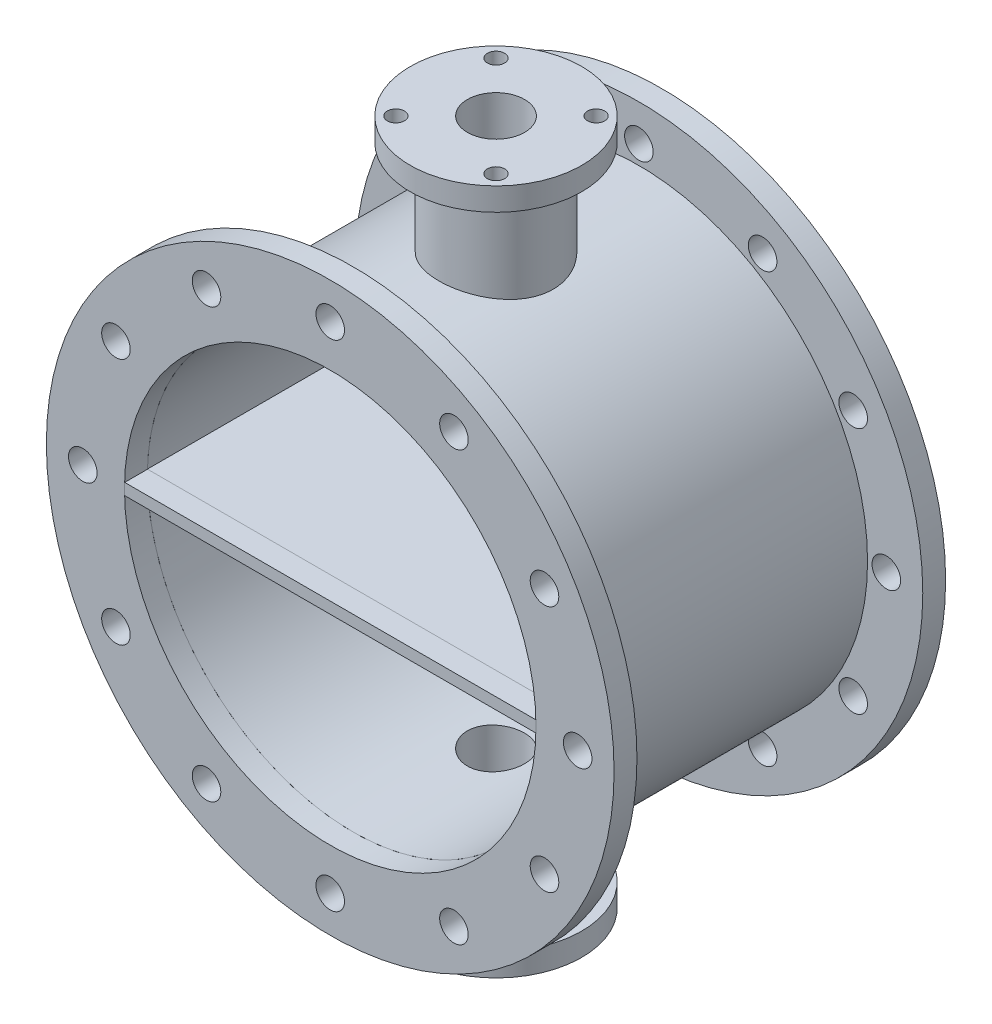
SolidWorks part; units mm, degrees
ref_plane "Front Plane" through (0, 0, 0) normal (0, 0, 1) x (1, 0, 0)
ref_plane "Top Plane" through (0, 0, 0) normal (0, 1, 0) x (1, 0, 0)
ref_plane "Right Plane" through (0, 0, 0) normal (1, 0, 0) x (0, 0, -1)
sketch "Sketch1" plane through (0, 0, 0) normal (0, 0, 1) x (1, 0, 0)
  line L1 (-179.9305, 5) -> (179.9305, 5)
  line L2 (-179.9305, -5) -> (179.9305, -5)
  circle A0 centre (0, 0) radius 200
  arc A1 (-179.9305, -5) -> (179.9305, -5) centre (0, 0) ccw
  arc A2 (179.9305, 5) -> (-179.9305, 5) centre (0, 0) ccw
  point P7 (0, 0)
  point P10 (0, 5)
  point P13 (0, -5)
extrude "Boss-Extrude1" add sketch "Sketch1" along normal blind 250
ref_plane "Plane2" through (0, 0, 125) normal (0, 0, 1) x (1, 0, 0)
sketch "Sketch3" plane through (0, 0, 125) normal (0, 0, 1) x (1, 0, 0)
  line L0 (-25, 193.6492) -> (-25, 300)
  line L1 (-25, 300) -> (-75, 300)
  line L2 (-25, 300) -> (-75, 300) construction
  line L3 (-75, 300) -> (-75, 280) construction
  line L4 (-75, 280) -> (-50, 280) construction
  line L5 (-50, 193.6492) -> (-25, 193.6492) construction
  line L6 (-50, 280) -> (-50, 193.6492) construction
  line L7 (-25, 193.6492) -> (-25, 300) construction
  line L8 (-75, 300) -> (-75, 280)
  line L9 (-75, 280) -> (-50, 280)
  line L10 (-50, 280) -> (-50, 193.6492)
  line L11 (-50, 193.6492) -> (-25, 193.6492)
  line L12 (0, 0) -> (0, 300) construction
  line L13 (0, 0) -> (200, 0) construction
  line L14 (-50, -280) -> (-50, -193.6492)
  line L15 (-75, -280) -> (-50, -280)
  line L16 (-75, -300) -> (-75, -280)
  line L17 (-25, -300) -> (-75, -300)
  line L18 (-25, -193.6492) -> (-25, -300)
  line L19 (-50, -193.6492) -> (-25, -193.6492)
  circle A0 centre (0, 0) radius 200 construction
  dimension "D1" = 86.3508
revolve "Revolve2" add sketch "Sketch3" angle 360 about L12
sketch "Sketch4" plane through (0, 300, 0) normal (0, 1, 0) x (1, 0, 0)
  line L0 (0, -125) -> (18.6125, -108.3094)
  circle A1 centre (0, -125) radius 25 construction
  circle A2 centre (43.7923, -81.2077) radius 7.5
  circle A3 centre (43.7923, -168.7923) radius 7.5
  circle A4 centre (-43.7923, -168.7923) radius 7.5
  circle A5 centre (-43.7923, -81.2077) radius 7.5
  point P16 (0, -125)
  dimension "D1" = 4
extrude "Cut-Extrude1" cut sketch "Sketch4" against normal blind 20 contours A5 | A2 | A3 | A4
mirror "Mirror1" about plane through (0, 0, 0) normal (0, 1, 0) of "Cut-Extrude1"
sketch "Sketch5" plane through (0, 300, 0) normal (0, 1, 0) x (1, 0, 0)
  line L0 (-220, -125) -> (220, -125) construction
  circle A0 centre (0, -125) radius 25
extrude "Cut-Extrude2" cut sketch "Sketch5" against normal blind 158
sketch "Sketch6" plane through (0, -300, 0) normal (0, -1, 0) x (1, 0, 0)
  circle A0 centre (0, 125) radius 25
extrude "Cut-Extrude3" cut sketch "Sketch6" against normal blind 158
sketch "Sketch7" plane through (0, 0, 250) normal (0, 0, 1) x (1, 0, 0)
  line L1 (-179.9305, -5) -> (179.9305, -5)
  line L2 (-179.9305, -5) -> (-179.9305, 5)
  line L3 (-179.9305, 5) -> (179.9305, 5)
  line L4 (179.9305, -5) -> (179.9305, 5)
  line L5 (-179.9305, -5) -> (179.9305, 5) construction
  line L6 (-179.9305, 5) -> (179.9305, -5) construction
  circle A1 centre (0, 0) radius 248.3003
  circle A2 centre (0, 0) radius 180
  circle A3 centre (0, 216.4273) radius 12.5
  circle A4 centre (108.2137, 187.4315) radius 12.5
  circle A5 centre (187.4315, 108.2137) radius 12.5
  circle A6 centre (216.4273, 0) radius 12.5
  circle A7 centre (187.4315, -108.2137) radius 12.5
  circle A8 centre (108.2137, -187.4315) radius 12.5
  circle A9 centre (0, -216.4273) radius 12.5
  circle A10 centre (-108.2137, -187.4315) radius 12.5
  circle A11 centre (-187.4315, -108.2137) radius 12.5
  circle A12 centre (-216.4273, 0) radius 12.5
  circle A13 centre (-187.4315, 108.2137) radius 12.5
  circle A14 centre (-108.2137, 187.4315) radius 12.5
  point P36 (0, 0)
  circle M6 centre (0, 0) radius 200
  line M7 (179.9305, 5) -> (-179.9305, 5)
  arc M8 (-179.9305, 5) -> (179.9305, 5) centre (0, 0) cw
  line M9 (-179.9305, -5) -> (179.9305, -5)
  arc M10 (179.9305, -5) -> (-179.9305, -5) centre (0, 0) cw
  dimension "D1" = 12
extrude "Boss-Extrude5" add sketch "Sketch7" along normal blind 20 separate body contours A1 A14 A13 A12 A11 A10 A9 A8 A7 A6 A5 A4 A3 M6 | L4 L2 M9 M7 | A2 M6 M8 M10
sketch "Sketch8" plane through (0, 0, 0) normal (0, 0, -1) x (-1, 0, 0)
  line L1 (-179.9305, -5) -> (179.9305, -5)
  line L2 (-179.9305, -5) -> (-179.9305, 5)
  line L3 (-179.9305, 5) -> (179.9305, 5)
  line L4 (179.9305, -5) -> (179.9305, 5)
  line L5 (-179.9305, -5) -> (179.9305, 5) construction
  line L6 (-179.9305, 5) -> (179.9305, -5) construction
  circle A0 centre (0, 0) radius 248.3003
  circle A1 centre (0, 0) radius 180
  circle A2 centre (-216.4273, 0) radius 12.5
  circle A3 centre (-187.4315, 108.2137) radius 12.5
  circle A4 centre (-108.2137, 187.4315) radius 12.5
  circle A5 centre (0, 216.4273) radius 12.5
  circle A6 centre (108.2137, 187.4315) radius 12.5
  circle A7 centre (187.4315, 108.2137) radius 12.5
  circle A8 centre (216.4273, 0) radius 12.5
  circle A9 centre (187.4315, -108.2137) radius 12.5
  circle A10 centre (108.2137, -187.4315) radius 12.5
  circle A11 centre (0, -216.4273) radius 12.5
  circle A12 centre (-108.2137, -187.4315) radius 12.5
  circle A13 centre (-187.4315, -108.2137) radius 12.5
  point P36 (0, 0)
  arc M3 (-179.9305, 5) -> (179.9305, 5) centre (0, 0) cw
  line M4 (179.9305, 5) -> (-179.9305, 5)
  circle M5 centre (0, 0) radius 200
  arc M6 (179.9305, -5) -> (-179.9305, -5) centre (0, 0) cw
  line M7 (-179.9305, -5) -> (179.9305, -5)
  dimension "D1" = 12
extrude "Boss-Extrude7" add sketch "Sketch8" along normal blind 20 separate body contours A0 A13 A12 A11 A10 A9 A8 A7 A6 A5 A4 A3 A2 M5 | A1 M5 M3 M6 | L4 L2 M7 M4
